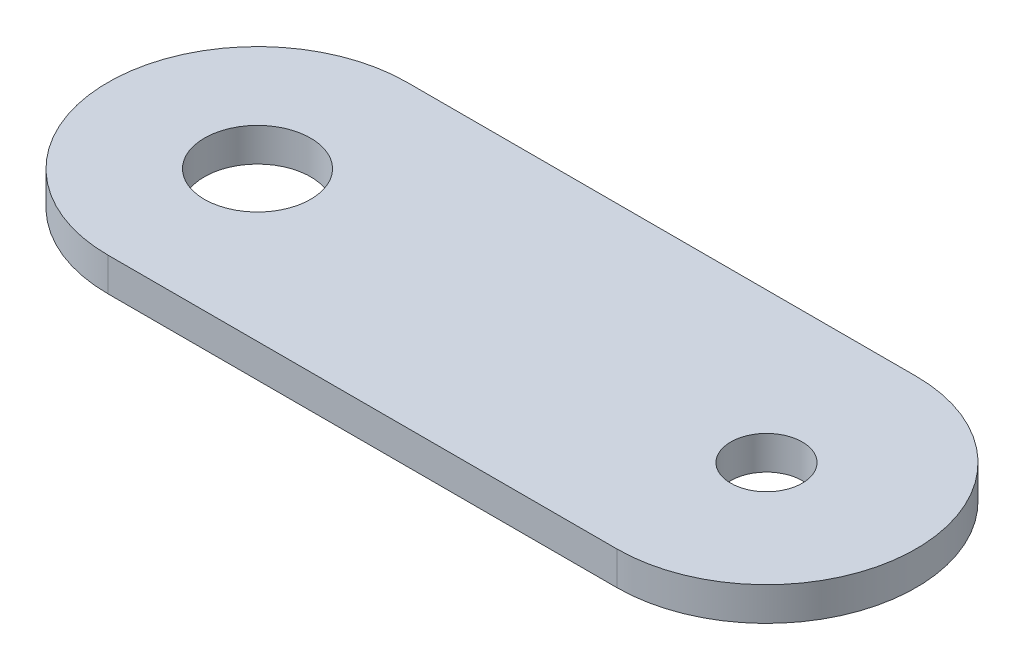
SolidWorks part; units mm, degrees
ref_plane "Front Plane" through (0, 0, 0) normal (0, 0, 1) x (1, 0, 0)
ref_plane "Top Plane" through (0, 0, 0) normal (0, 1, 0) x (1, 0, 0)
ref_plane "Right Plane" through (0, 0, 0) normal (1, 0, 0) x (0, 0, -1)
sketch "Sketch1" plane through (0, 0, 0) normal (0, 1, 0) x (1, 0, 0)
  line L0 (0, 0) -> (60.7048, 0) construction
  line L1 (0, 17.8414) -> (60.7048, 17.8414)
  line L2 (0, -17.8414) -> (60.7048, -17.8414)
  arc A0 (0, 17.8414) -> (0, -17.8414) centre (0, 0) ccw
  arc A1 (60.7048, -17.8414) -> (60.7048, 17.8414) centre (60.7048, 0) ccw
  circle A2 centre (0, 0) radius 5
  circle A3 centre (60.7048, 0) radius 2.5
  circle A4 centre (0, 0) radius 6.3321
  circle A5 centre (60.7048, 0) radius 4.2654
  point P3 (30.3524, 0)
extrude "Boss-Extrude1" add sketch "Sketch1" along normal blind 4
